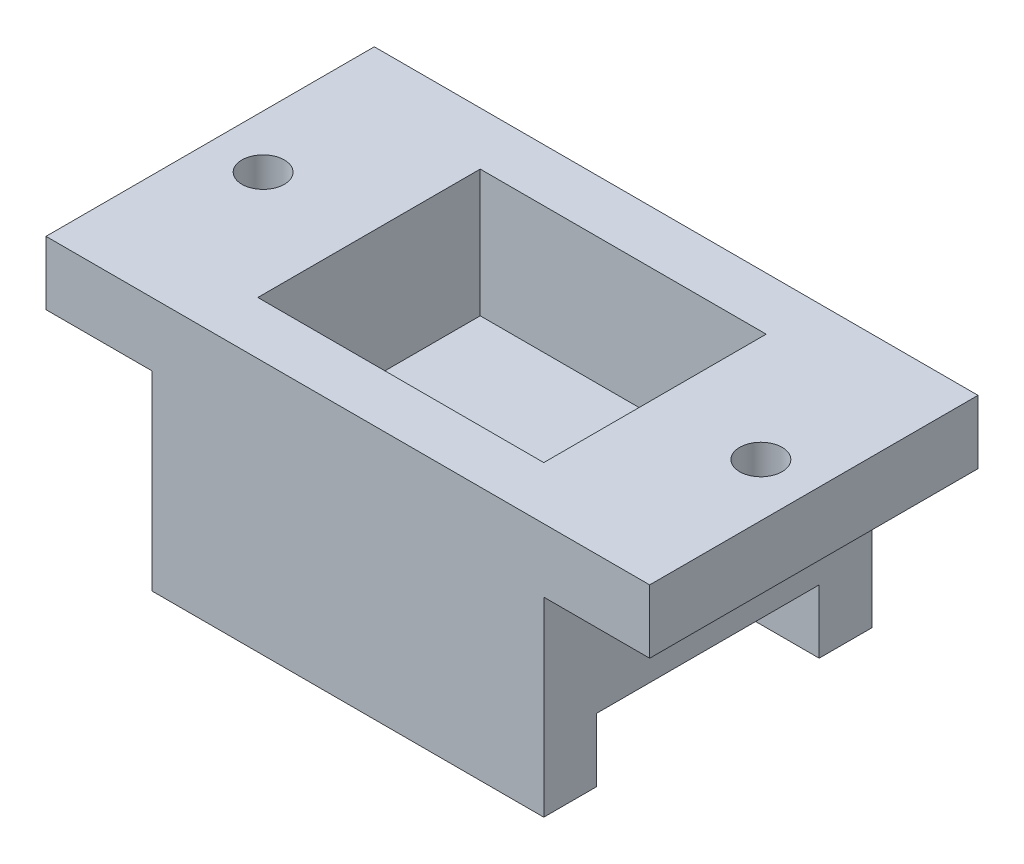
SolidWorks part; units mm, degrees
ref_plane "Front Plane" through (0, 0, 0) normal (0, 0, 1) x (1, 0, 0)
ref_plane "Top Plane" through (0, 0, 0) normal (0, 1, 0) x (1, 0, 0)
ref_plane "Right Plane" through (0, 0, 0) normal (1, 0, 0) x (0, 0, -1)
sketch "Sketch2" plane through (0, 0, 0) normal (0, 1, 0) x (1, 0, 0)
  line L1 (-12.8729, 6.7833) -> (5.6271, 6.7833)
  line L2 (-12.8729, 6.7833) -> (-12.8729, -8.7167)
  line L3 (-12.8729, -8.7167) -> (5.6271, -8.7167)
  line L4 (5.6271, 6.7833) -> (5.6271, -8.7167)
  line L5 (-12.8729, 6.7833) -> (5.6271, -8.7167) construction
  line L6 (-12.8729, -8.7167) -> (5.6271, 6.7833) construction
  point P0 (-3.6229, -0.9667)
  dimension "D1" = 18.5
  dimension "D2" = 15.5
extrude "Boss-Extrude1" add sketch "Sketch2" along normal blind 11
sketch "Sketch3" plane through (0, 11, 0) normal (0, 1, 0) x (1, 0, 0)
  line L1 (-12.8729, 6.7833) -> (5.6271, 6.7833)
  line L2 (-12.8729, 6.7833) -> (-12.8729, -8.7167)
  line L3 (-12.8729, -8.7167) -> (5.6271, -8.7167)
  line L4 (5.6271, 6.7833) -> (5.6271, -8.7167)
extrude "Boss-Extrude2" add sketch "Sketch3" along normal blind 3
sketch "Sketch4" plane through (0, 14, 0) normal (0, 1, 0) x (1, 0, 0)
  line L0 (5.6271, 6.7833) -> (-12.8729, 6.7833) construction
  line L1 (-10.3729, 4.2833) -> (3.1271, 4.2833)
  line L2 (-10.3729, 4.2833) -> (-10.3729, -6.2167)
  line L3 (-10.3729, -6.2167) -> (3.1271, -6.2167)
  line L4 (3.1271, 4.2833) -> (3.1271, -6.2167)
  line L5 (5.6271, -8.7167) -> (5.6271, 6.7833) construction
  dimension "D1" = 10.5
  dimension "D2" = 13.5
  dimension "D3" = 2.5
  dimension "D4" = 2.5
extrude "Cut-Extrude1" cut sketch "Sketch4" against normal blind 6
sketch "Sketch5" plane through (0, 8, 0) normal (0, 1, 0) x (1, 0, 0)
  line L0 (-10.3729, -6.2167) -> (3.1271, -6.2167) construction
  line L1 (3.1271, 4.2833) -> (0.1271, 4.2833)
  line L2 (3.1271, 4.2833) -> (3.1271, -6.2167)
  line L3 (3.1271, -6.2167) -> (0.1271, -6.2167)
  line L4 (0.1271, 4.2833) -> (0.1271, -6.2167)
  dimension "D1" = 3
extrude "Cut-Extrude2" cut sketch "Sketch5" against normal blind 26 contours L4 L3 L2 L1
sketch "Sketch10" plane through (0, 0, 8.7167) normal (0, 0, 1) x (1, 0, 0)
  line L0 (5.6271, 14) -> (5.6271, 0) construction
  line L1 (-12.8729, 0) -> (5.6271, 0)
  line L2 (-12.8729, 0) -> (-12.8729, 5)
  line L3 (-12.8729, 5) -> (5.6271, 5)
  line L4 (5.6271, 0) -> (5.6271, 5)
  dimension "D1" = 5
extrude "Cut-Extrude3" cut sketch "Sketch10" against normal blind 26
sketch "Sketch11" plane through (5.6271, 0, 0) normal (1, 0, 0) x (0, 0, -1)
  line L0 (6.7833, 14) -> (6.7833, 5) construction
  line L1 (-8.7167, 14) -> (6.7833, 14)
  line L2 (-8.7167, 14) -> (-8.7167, 11)
  line L3 (-8.7167, 11) -> (6.7833, 11)
  line L4 (6.7833, 14) -> (6.7833, 11)
  dimension "D1" = 3
extrude "Boss-Extrude3" add sketch "Sketch11" along normal blind 5
sketch "Sketch13" plane through (0, 5, 0) normal (0, -1, 0) x (1, 0, 0)
  line L0 (-12.8729, -6.7833) -> (-12.8729, 8.7167) construction
  line L1 (5.6271, 8.7167) -> (-12.8729, 8.7167)
  line L2 (5.6271, 8.7167) -> (5.6271, 6.2179)
  line L3 (5.6271, 6.2179) -> (-12.8729, 6.2179)
  line L4 (-12.8729, 8.7167) -> (-12.8729, 6.2179)
  line L6 (5.6271, -6.7833) -> (-12.8729, -6.7833)
  line L7 (5.6271, -6.7833) -> (5.6271, -4.2846)
  line L8 (5.6271, -4.2846) -> (-12.8729, -4.2846)
  line L9 (-12.8729, -6.7833) -> (-12.8729, -4.2846)
  line L10 (-12.8729, 6.2179) -> (0.1271, 6.2179)
  line L11 (-12.8729, 6.2179) -> (-12.8729, -4.2833)
  line L12 (-12.8729, -4.2833) -> (0.1271, -4.2833)
  line L13 (0.1271, 6.2179) -> (0.1271, -4.2833)
  line M1 (0.1271, -4.2833) -> (0.1271, 6.2167)
  line M5 (5.6271, -6.7833) -> (5.6271, 8.7167)
  line M6 (5.6271, 8.7167) -> (-12.8729, 8.7167)
  line M7 (-12.8729, 8.7167) -> (-12.8729, -6.7833)
  line M8 (-12.8729, -6.7833) -> (5.6271, -6.7833)
extrude "Boss-Extrude4" add sketch "Sketch13" along normal blind 3 contours L3 M5 M6 M7 | L13 L3 L12 M7 M1 | L8 M5 M7 M8
sketch "Sketch14" plane through (-12.8729, 0, 0) normal (-1, 0, 0) x (0, 0, 1)
  line L0 (8.7167, 14) -> (8.7167, 2) construction
  line L1 (-6.7833, 14) -> (8.7167, 14)
  line L2 (-6.7833, 14) -> (-6.7833, 11)
  line L3 (-6.7833, 11) -> (8.7167, 11)
  line L4 (8.7167, 14) -> (8.7167, 11)
  dimension "D1" = 3
extrude "Boss-Extrude6" add sketch "Sketch14" along normal blind 5 contours L3 L4 L1 L2
sketch "Sketch16" plane through (0, 14, 0) normal (0, 1, 0) x (1, 0, 0)
  line L0 (-17.8729, 6.7833) -> (-17.8729, -8.7167) construction
  line L1 (10.6271, 6.7833) -> (10.6271, -8.7167) construction
  circle A0 centre (-15.3729, -0.9667) radius 1
  circle A1 centre (8.1271, -0.9667) radius 1
  point P6 (0, 0)
  point P7 (0, 0)
  point P8 (0, 0)
  point P9 (7.6242, -0.9667)
  dimension "D1" = 2
  dimension "D2" = 2.5
  dimension "D3" = 2
  dimension "D4" = 2.5
extrude "Cut-Extrude5" cut sketch "Sketch16" against normal blind 5 contours A0 | A1
